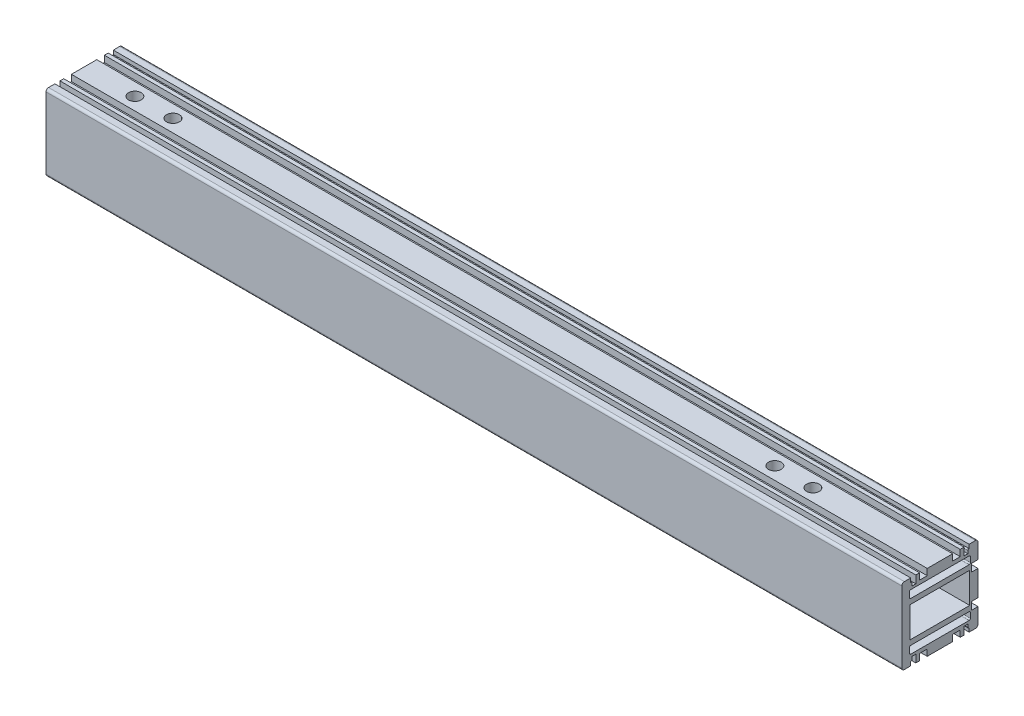
SolidWorks part; units mm, degrees
ref_plane "前视基准面" through (0, 0, 0) normal (0, 0, 1) x (1, 0, 0)
ref_plane "上视基准面" through (0, 0, 0) normal (0, 1, 0) x (1, 0, 0)
ref_plane "右视基准面" through (0, 0, 0) normal (1, 0, 0) x (0, 0, -1)
sketch "草图1" plane through (0, 0, 0) normal (1, 0, 0) x (0, 0, -1)
  line L0 (-15, 15) -> (15, -15) construction
  line L1 (-14, 15) -> (-11.5, 15)
  line L2 (-15, 14) -> (-15, -14)
  line L3 (-14, -15) -> (-11.5, -15)
  line L4 (15, 14) -> (15, 8)
  line L5 (15, 15) -> (-15, -15) construction
  line L6 (-11.5, 15) -> (-11.5, 13.5)
  line L7 (-11.5, 13.5) -> (-11.4, 13.5)
  line L8 (-11, 13.1) -> (-11, 12)
  line L9 (-11, 12) -> (-9.5, 12)
  line L10 (-9.5, 12) -> (-9.5, 15)
  line L11 (-9.5, 15) -> (-8, 15)
  line L12 (-8, 15) -> (-8, 12.5)
  line L13 (-8, 12.5) -> (-5, 12.5)
  line L14 (-5, 12.5) -> (-5, 15)
  line L15 (-5, 15) -> (5, 15)
  line L16 (0, 21.5201) -> (0, -18.309) construction
  line L17 (0, 55) -> (0, -55) construction
  line L18 (5, 12.5) -> (5, 15)
  line L19 (8, 12.5) -> (5, 12.5)
  line L20 (8, 15) -> (8, 12.5)
  line L21 (9.5, 15) -> (8, 15)
  line L22 (9.5, 12) -> (9.5, 15)
  line L23 (11, 12) -> (9.5, 12)
  line L24 (11, 13.1) -> (11, 12)
  line L25 (11.5, 13.5) -> (11.4, 13.5)
  line L26 (11.5, 15) -> (11.5, 13.5)
  line L27 (8, 15) -> (9.5, 15)
  line L28 (11.5, 15) -> (14, 15)
  line L29 (-19.8303, 0) -> (22.13, 0) construction
  line L30 (55, 0) -> (-55, 0) construction
  line L31 (8, -15) -> (9.5, -15)
  line L32 (11.5, -15) -> (11.5, -13.5)
  line L33 (11.5, -13.5) -> (11.4, -13.5)
  line L34 (11, -13.1) -> (11, -12)
  line L35 (11, -12) -> (9.5, -12)
  line L36 (9.5, -12) -> (9.5, -15)
  line L37 (9.5, -15) -> (8, -15)
  line L38 (8, -15) -> (8, -12.5)
  line L39 (8, -12.5) -> (5, -12.5)
  line L40 (5, -12.5) -> (5, -15)
  line L41 (-5, -15) -> (5, -15)
  line L42 (-5, -12.5) -> (-5, -15)
  line L43 (-8, -12.5) -> (-5, -12.5)
  line L44 (-8, -15) -> (-8, -12.5)
  line L45 (-9.5, -15) -> (-8, -15)
  line L46 (-9.5, -12) -> (-9.5, -15)
  line L47 (-11, -12) -> (-9.5, -12)
  line L48 (-11, -13.1) -> (-11, -12)
  line L49 (-11.5, -13.5) -> (-11.4, -13.5)
  line L50 (-11.5, -15) -> (-11.5, -13.5)
  line L51 (-9.5, -15) -> (-8, -15)
  line L52 (-5, -15) -> (5, -15)
  line L53 (8, -15) -> (9.5, -15)
  line L54 (11.5, -15) -> (14, -15)
  line L55 (15, 8) -> (12.5, 8)
  line L56 (12.5, 8) -> (12.5, 5)
  line L57 (12.5, 5) -> (15, 5)
  line L58 (12.5, -5) -> (15, -5)
  line L59 (12.5, -8) -> (12.5, -5)
  line L60 (15, -8) -> (12.5, -8)
  line L61 (15, 5) -> (15, -5)
  line L62 (15, -8) -> (15, -14)
  line L63 (12, -10.5) -> (12, -8.5)
  line L64 (-11.5, 11) -> (11.5, 11)
  line L65 (-12, 10.5) -> (-12, 8.5)
  line L66 (-11.5, 8) -> (11.5, 8)
  line L67 (12, 10.5) -> (12, 8.5)
  line L68 (-11.5, -8) -> (11.5, -8)
  line L69 (-12, -10.5) -> (-12, -8.5)
  line L70 (-11.5, -11) -> (11.5, -11)
  line L72 (-11.75, 6) -> (11.75, 6)
  line L73 (-11.75, 6) -> (-11.75, -6)
  line L74 (-11.75, -6) -> (11.75, -6)
  line L75 (11.75, 6) -> (11.75, -6)
  arc A0 (12, 8.5) -> (11.5, 8) centre (11.5, 8.5) cw
  arc A1 (11.5, 11) -> (12, 10.5) centre (11.5, 10.5) cw
  arc A2 (-11.5, 11) -> (-12, 10.5) centre (-11.5, 10.5) ccw
  arc A3 (-11.5, 8) -> (-12, 8.5) centre (-11.5, 8.5) cw
  arc A4 (-11, -13.1) -> (-11.4, -13.5) centre (-11.4, -13.1) cw
  arc A5 (11.4, -13.5) -> (11, -13.1) centre (11.4, -13.1) cw
  arc A6 (11.4, 13.5) -> (11, 13.1) centre (11.4, 13.1) ccw
  arc A7 (-11, 13.1) -> (-11.4, 13.5) centre (-11.4, 13.1) ccw
  arc A8 (-11.5, -8) -> (-12, -8.5) centre (-11.5, -8.5) ccw
  arc A9 (-11.5, -11) -> (-12, -10.5) centre (-11.5, -10.5) cw
  arc A10 (11.5, -11) -> (12, -10.5) centre (11.5, -10.5) ccw
  arc A11 (12, -8.5) -> (11.5, -8) centre (11.5, -8.5) ccw
  arc A12 (14, 15) -> (15, 14) centre (14, 14) cw
  arc A13 (14, -15) -> (15, -14) centre (14, -14) ccw
  arc A14 (-15, -14) -> (-14, -15) centre (-14, -14) ccw
  arc A15 (-15, 14) -> (-14, 15) centre (-14, 14) cw
  point P69 (12, 11)
  point P72 (-12, 11)
  point P77 (-11, -13.5)
  point P80 (11, -13.5)
  point P83 (11, 13.5)
  point P86 (-11, 13.5)
  point P99 (-12, -11)
  point P100 (12, -11)
  dimension "D17" = 0.5
  dimension "D18" = 0.4
  dimension "D21" = 1
  dimension "D1" = 3.5
  dimension "D2" = 1.5
  dimension "D3" = 0.5
  dimension "D4" = 1.5
  dimension "D5" = 3
  dimension "D6" = 30
  dimension "D7" = 30
  dimension "D8" = 1.5
  dimension "D9" = 2.5
  dimension "D10" = 3
  dimension "D11" = 2.5
  dimension "D12" = 7
  dimension "D13" = 3
  dimension "D14" = 4
  dimension "D15" = 3
  dimension "D16" = 24
  dimension "D19" = 23.5
  dimension "D20" = 12
extrude "凸台-拉伸1" add sketch "草图1" along normal mid plane 337 contours A15 L2 A14 L3 L50 L49 A4 L48 L47 L46 L45 L44 L43 L42 L41 L40 L39 L38 L31 L36 L35 L34 A5 L33 L32 L54 A13 L62 L60 L59 L58 L61 L57 L56 L55 L4 A12 L28 L26 L25 A6 L24 L23 L22 L21 L20 L19 L18 L15 L14 L13
hole_wizard "M6 螺纹孔1" positions "草图3" profile "草图2" tap size "M6" standard "GB"
sketch "草图3" plane through (0, 15, 0) normal (0, 1, 0) x (-1, 0, 0)
  line L0 (168.5, 5) -> (168.5, -5) construction
  line L1 (-168.5, 15) -> (168.5, 15) construction
  point P0 (148.5, 0)
  point P1 (133.5, 0)
  point P4 (-103.5, 0)
  point P7 (-118.5, 0)
  dimension "D1" = 20
  dimension "D2" = 15
sketch "草图2" plane through (-148.5, 15, 0) normal (1, 0, 0) x (0, 0, 1)
  line L0 (0, 0) -> (0, 16.5022)
  line L1 (0, 16.5022) -> (2.5, 15)
  line L2 (2.5, 15) -> (2.5, 0)
  line L5 (2.5, 0) -> (0, 0)
  line L10 (0, 16.5022) -> (-2.5, 15) construction
  line L11 (0, -6.35) -> (0, 107.95) construction
  dimension "螺纹孔钻头直径" = 5
  dimension "螺纹孔钻头深度" = 15
  dimension "导头角度" = 118
cosmetic thread "孔螺蚊线1" parameters "D1"=9, "D2"=6
cosmetic thread "孔螺蚊线2" parameters "D1"=9, "D2"=6
cosmetic thread "孔螺蚊线3" parameters "D1"=9, "D2"=6
cosmetic thread "孔螺蚊线4" parameters "D1"=9, "D2"=6
